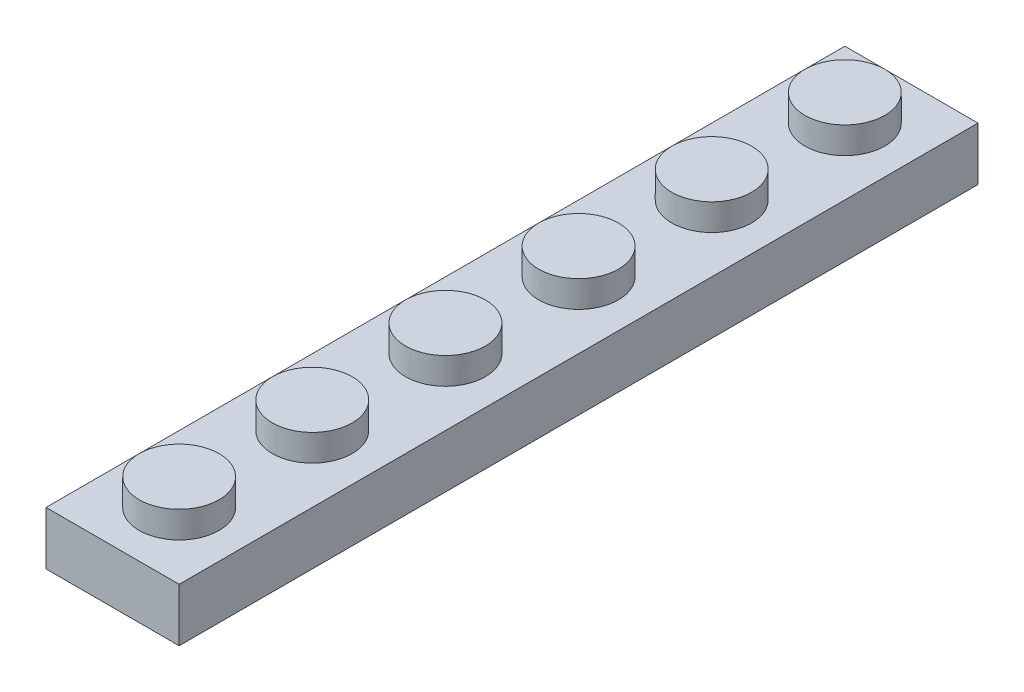
SolidWorks part; units mm, degrees
ref_plane "Front Plane" through (0, 0, 0) normal (0, 0, 1) x (1, 0, 0)
ref_plane "Top Plane" through (0, 0, 0) normal (0, 1, 0) x (1, 0, 0)
ref_plane "Right Plane" through (0, 0, 0) normal (1, 0, 0) x (0, 0, -1)
sketch "Sketch1" plane through (0, 0, 0) normal (0, 1, 0) x (1, 0, 0)
  line L1 (0, 0) -> (8, 0)
  line L2 (0, 0) -> (0, 48)
  line L3 (0, 48) -> (8, 48)
  line L4 (8, 0) -> (8, 48)
  dimension "D1" = 8
  dimension "D2" = 48
extrude "Boss-Extrude1" add sketch "Sketch1" along normal blind 3.2
sketch "Sketch2" plane through (0, 3.2, 0) normal (0, 1, 0) x (1, 0, 0)
  line L0 (4, 0) -> (4, 48) construction
  line L1 (0, 0) -> (8, 0) construction
  line L2 (8, 48) -> (0, 48) construction
  line L3 (8, 0) -> (8, 4) construction
  line L4 (8, 0) -> (8, 48) construction
  line L5 (8, 4) -> (4, 4) construction
  circle A0 centre (4, 4) radius 2.4
  dimension "D3" = 4.8
  dimension "D1" = 4
  dimension "D2" = 4
extrude "Boss-Extrude2" add sketch "Sketch2" along normal blind 1.6
pattern_linear "LPattern1" count 2 spacing 8 along (1, 0, 0) count 6 spacing 8 along (0, 0, -1) of "Boss-Extrude2"
shell "Shell1" thickness 1.6
